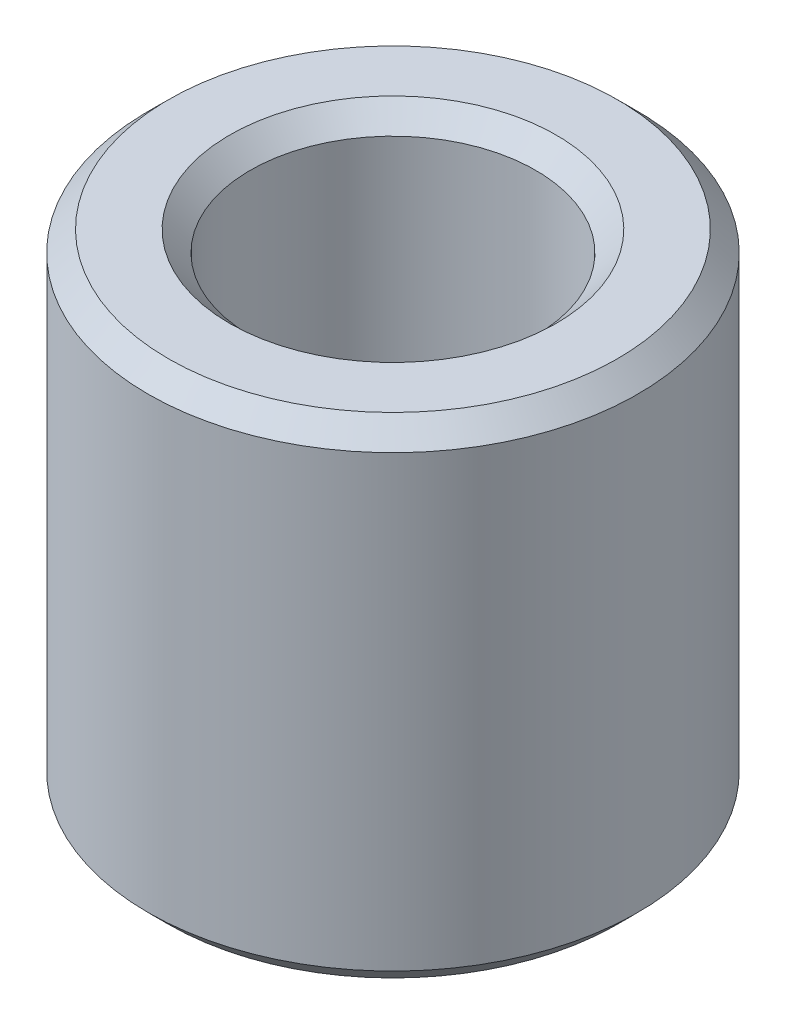
SolidWorks part; units mm, degrees
ref_plane "Front Plane" through (0, 0, 0) normal (0, 0, 1) x (1, 0, 0)
ref_plane "Top Plane" through (0, 0, 0) normal (0, 1, 0) x (1, 0, 0)
ref_plane "Right Plane" through (0, 0, 0) normal (1, 0, 0) x (0, 0, -1)
sketch "Sketch1" plane through (0, 0, 0) normal (0, 1, 0) x (1, 0, 0)
  circle A0 centre (0, 0) radius 1.75
  circle A1 centre (0, 0) radius 3
  dimension "D1" = 3.5
  dimension "D2" = 6
extrude "Boss-Extrude1" add sketch "Sketch1" along normal blind 6
chamfer "Chamfer1" distance 0.25 angle 45 4 edges at (0, 6, 1.75) (0, 0, 1.75) (0, 0, 3) (0, 6, 3)
